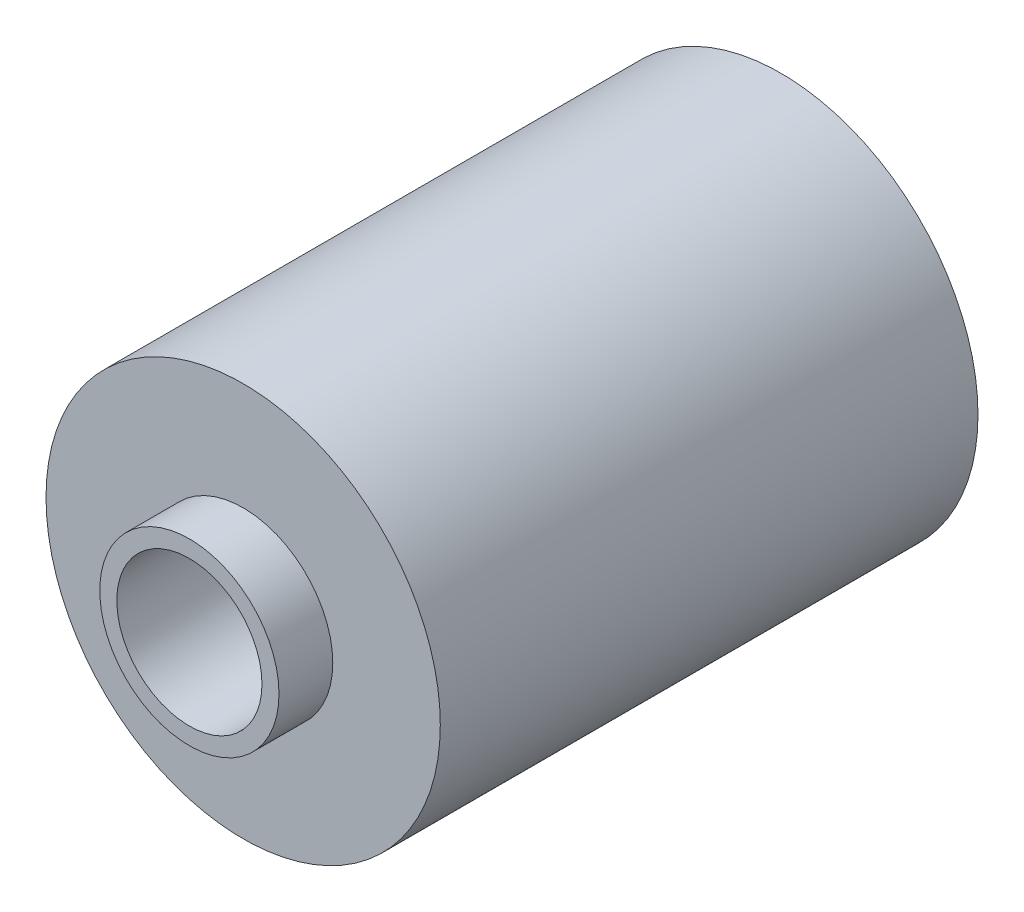
SolidWorks part; units mm, degrees
ref_plane "Alzado" through (0, 0, 0) normal (0, 0, 1) x (1, 0, 0)
ref_plane "Planta" through (0, 0, 0) normal (0, 1, 0) x (1, 0, 0)
ref_plane "Vista lateral" through (0, 0, 0) normal (1, 0, 0) x (0, 0, -1)
sketch "Croquis1" plane through (0, 0, 0) normal (0, 0, 1) x (1, 0, 0)
  circle A0 centre (0, 0) radius 11
  dimension "D1" = 22
extrude "Saliente-Extruir1" add sketch "Croquis1" along normal mid plane 30
sketch "Croquis3" plane through (0, 0, 15) normal (0, 0, 1) x (1, 0, 0)
  circle A0 centre (0, 0) radius 5
  dimension "D1" = 10
extrude "Saliente-Extruir2" add sketch "Croquis3" along normal blind 3
sketch "Croquis2" plane through (0, 0, 15) normal (0, 0, 1) x (1, 0, 0)
  circle A0 centre (0, 0) radius 4.05
extrude "Cortar-Extruir1" cut sketch "Croquis2" against normal mid plane 578
